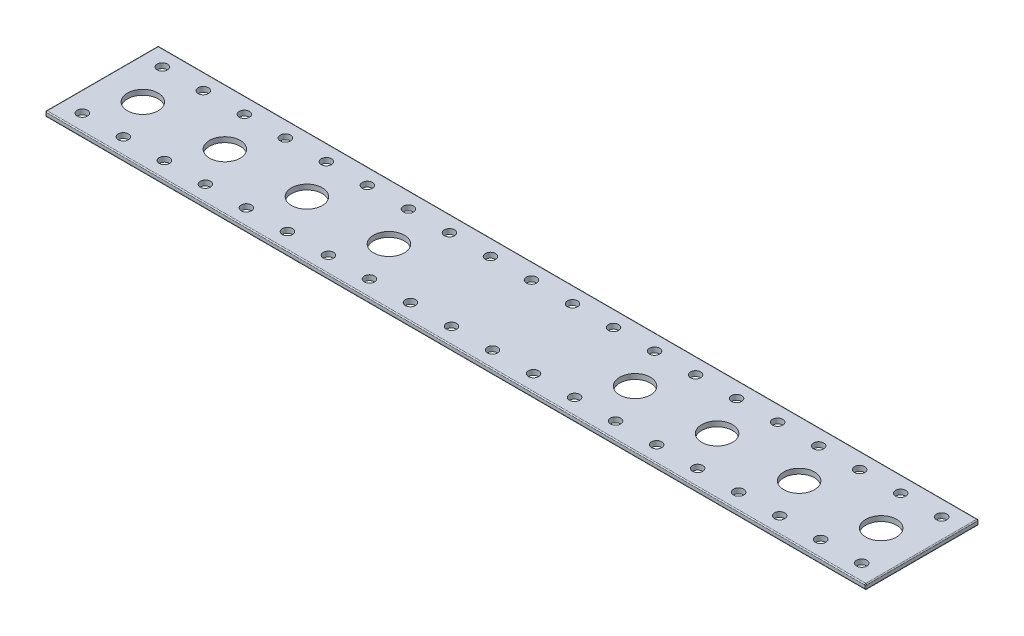
SolidWorks part; units mm, degrees
ref_plane "Front Plane" through (0, 0, 0) normal (0, 0, 1) x (1, 0, 0)
ref_plane "Top Plane" through (0, 0, 0) normal (0, 1, 0) x (1, 0, 0)
ref_plane "Right Plane" through (0, 0, 0) normal (1, 0, 0) x (0, 0, -1)
sketch "Sketch1" plane through (0, 0, 0) normal (0, 1, 0) x (1, 0, 0)
  line L1 (-200, -27.5) -> (200, -27.5)
  line L2 (-200, -27.5) -> (-200, 27.5)
  line L3 (-200, 27.5) -> (200, 27.5)
  line L4 (200, -27.5) -> (200, 27.5)
  line L5 (-200, -27.5) -> (200, 27.5) construction
  line L6 (-200, 27.5) -> (200, -27.5) construction
  point P0 (0, 0)
  dimension "D1" = 400
  dimension "D2" = 55
extrude "Boss-Extrude1" add sketch "Sketch1" along normal blind 2.5
sketch "Sketch2" plane through (0, 2.5, 0) normal (0, 1, 0) x (1, 0, 0)
  line L2 (-200, 27.5) -> (-200, -27.5) construction
  line L3 (200, 27.5) -> (-200, 27.5) construction
  line L4 (-200, -27.5) -> (200, -27.5) construction
  circle A1 centre (-190, 19.5) radius 2.5
  circle A2 centre (-170, 19.5) radius 2.5
  circle A5 centre (-190, -19.5) radius 2.5
  circle A6 centre (-170, -19.5) radius 2.5
  point P15 (-175.6111, -23.2609)
  point P16 (0, 0)
  dimension "D1" = 20
  dimension "D2" = 5
  dimension "D3" = 5
  dimension "D6" = 5
  dimension "D7" = 5
  dimension "D9" = 20
  dimension "D4" = 10
  dimension "D5" = 8
  dimension "D8" = 10
  dimension "D10" = 8
extrude "Cut-Extrude1" cut sketch "Sketch2" against normal up to surface (2.5 mm away) up to face at (0, 0, 0)
pattern_linear "LPattern1" count 10 spacing 40 along (1, 0, 0) of "Cut-Extrude1"
sketch "Sketch3" plane through (0, 2.5, 0) normal (0, 1, 0) x (1, 0, 0)
  line L0 (-190, 19.5) -> (-170, -19.5) construction
  line L1 (-190, -19.5) -> (-170, 19.5) construction
  circle A0 centre (-180, 0) radius 7.5
  dimension "D1" = 15
extrude "Cut-Extrude2" cut sketch "Sketch3" against normal up to surface (2.5 mm away) up to face at (-130, 0, 17)
pattern_linear "LPattern2" count 4 spacing 40 along (1, 0, 0) of "Cut-Extrude2"
mirror "Mirror1" about plane through (0, 0, 0) normal (1, 0, 0) of "LPattern2", "Cut-Extrude2"
fillet "Fillet1" radius 0.5 12 edges at (200, 2.5, 0) (200, 0, 0) (200, 1.25, -27.5) (0, 2.5, -27.5) (0, 0, -27.5) (-200, 1.25, -27.5) (-200, 2.5, 0) (-200, 0, 0) (-200, 1.25, 27.5) (0, 2.5, 27.5) (200, 1.25, 27.5) (0, 0, 27.5)
